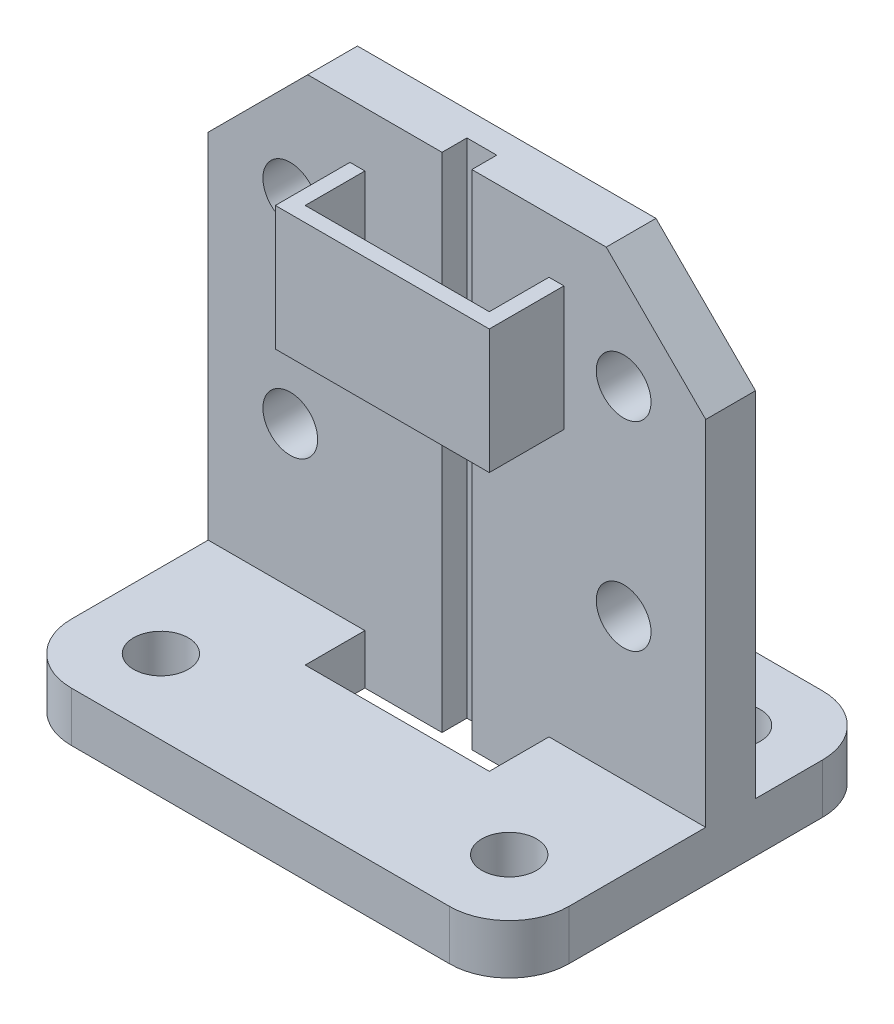
SolidWorks part; units mm, degrees
ref_plane "Front Plane" through (0, 0, 0) normal (0, 0, 1) x (1, 0, 0)
ref_plane "Top Plane" through (0, 0, 0) normal (0, 1, 0) x (1, 0, 0)
ref_plane "Right Plane" through (0, 0, 0) normal (1, 0, 0) x (0, 0, -1)
sketch "Sketch1" plane through (0, 0, 0) normal (0, 0, 1) x (1, 0, 0)
  line L1 (12.7, -10.795) -> (-12.7, -10.795)
  line L2 (12.7, -10.795) -> (12.7, 10.795)
  line L3 (12.7, 10.795) -> (-12.7, 10.795)
  line L4 (-12.7, -10.795) -> (-12.7, 10.795)
  line L5 (12.7, -10.795) -> (-12.7, 10.795) construction
  line L6 (12.7, 10.795) -> (-12.7, -10.795) construction
  line L7 (8.509, -5.08) -> (-8.509, -5.08) construction
  line L8 (8.509, -5.08) -> (8.509, 5.08) construction
  line L9 (8.509, 5.08) -> (-8.509, 5.08) construction
  line L10 (-8.509, -5.08) -> (-8.509, 5.08) construction
  line L11 (8.509, -5.08) -> (-8.509, 5.08) construction
  line L12 (8.509, 5.08) -> (-8.509, -5.08) construction
  circle A0 centre (-8.509, 5.08) radius 1.397
  circle A1 centre (8.509, 5.08) radius 1.397
  circle A2 centre (8.509, -5.08) radius 1.397
  circle A3 centre (-8.509, -5.08) radius 1.397
  point P0 (0, 0)
  point P6 (0, 0)
  dimension "D5" = 2.794
  dimension "D1" = 25.4
  dimension "D2" = 21.59
  dimension "D3" = 17.018
  dimension "D4" = 10.16
extrude "Boss-Extrude1" add sketch "Sketch1" along normal blind 2.54
sketch "Sketch2" plane through (0, 0, 2.54) normal (0, 0, 1) x (1, 0, 0)
  line L0 (12.7, 10.795) -> (-12.7, 10.795) construction
  line L1 (0.762, -10.795) -> (-0.762, -10.795)
  line L2 (0.762, -10.795) -> (0.762, 10.795)
  line L3 (0.762, 10.795) -> (-0.762, 10.795)
  line L4 (-0.762, -10.795) -> (-0.762, 10.795)
  line L5 (0.762, -10.795) -> (-0.762, 10.795) construction
  line L6 (0.762, 10.795) -> (-0.762, -10.795) construction
  point P0 (0, 0)
  dimension "D1" = 1.524
extrude "Cut-Extrude1" cut sketch "Sketch2" against normal blind 1.27
ref_plane "Plane1" through (0, -1.905, 0) normal (0, -1, 0) x (-1, 0, 0)
sketch "Sketch5" plane through (0, -1.905, 0) normal (0, -1, 0) x (-1, 0, 0)
  line L0 (-4.445, -2.54) -> (-4.445, -5.334)
  line L1 (-0.762, -2.54) -> (-12.7, -2.54) construction
  line L2 (-4.445, -5.334) -> (4.445, -5.334)
  line L3 (4.445, -5.334) -> (4.445, -2.54)
  line L4 (12.7, -2.54) -> (0.762, -2.54) construction
  line L5 (4.445, -2.54) -> (0.762, -2.54) construction
  line L9 (-0.762, -2.54) -> (-4.445, -2.54) construction
  line L10 (-4.445, -2.54) -> (-4.699, -2.54)
  line L11 (-4.699, -2.54) -> (-4.699, -5.588)
  line L12 (-4.699, -5.588) -> (4.699, -5.588)
  line L13 (4.699, -5.588) -> (4.699, -2.54)
  line L14 (4.699, -2.54) -> (4.445, -2.54)
  line L15 (0, 0) -> (0, -5.588) construction
  dimension "D1" = 8.89
  dimension "D2" = 2.794
  dimension "D3" = 0.254
  dimension "D4" = 0.254
sketch "Sketch7" plane through (0, -10.795, 0) normal (0, -1, 0) x (1, 0, 0)
  line L0 (-0.762, 2.54) -> (-12.7, 2.54)
  line L1 (-12.7, 2.54) -> (-12.7, 0)
  line L2 (-12.7, 0) -> (12.7, 0)
  line L3 (12.7, 0) -> (12.7, 2.54)
  line L4 (12.7, 2.54) -> (0.762, 2.54)
  line L5 (0.762, 2.54) -> (0.762, 1.27)
  line L6 (0.762, 1.27) -> (-0.762, 1.27)
  line L7 (-0.762, 1.27) -> (-0.762, 2.54)
extrude "Boss-Extrude3" add sketch "Sketch7" along normal blind 1.524
sketch "Sketch8" plane through (0, -12.319, 0) normal (0, -1, 0) x (1, 0, 0)
  line L0 (0, 3.048) -> (0, 0) construction
  line L1 (12.7, -6.477) -> (-12.7, -6.477)
  line L2 (12.7, -6.477) -> (12.7, 12.573)
  line L3 (12.7, 12.573) -> (-12.7, 12.573)
  line L4 (-12.7, -6.477) -> (-12.7, 12.573)
  line L5 (12.7, -6.477) -> (-12.7, 12.573) construction
  line L6 (12.7, 12.573) -> (-12.7, -6.477) construction
  line L8 (-12.7, 0) -> (12.7, 0) construction
  circle A0 centre (-8.89, 8.763) radius 1.397
  circle A1 centre (8.89, 8.763) radius 1.397
  circle A2 centre (-8.89, -2.667) radius 1.397
  circle A3 centre (8.89, -2.667) radius 1.397
  point P0 (0, 3.048)
  dimension "D3" = 2.794
  dimension "D1" = 25.4
  dimension "D2" = 19.05
  dimension "D4" = 3.81
  dimension "D5" = 3.81
  dimension "D6" = 3.81
  dimension "D7" = 3.81
  dimension "D8" = 3.048
extrude "Boss-Extrude4" add sketch "Sketch8" along normal blind 2.54
extrude "Cut-Extrude2" cut sketch "Sketch5" along normal blind 15.24
sketch "Sketch9" plane through (0, -12.319, 0) normal (0, 1, 0) x (1, 0, 0)
  line L0 (-0.762, -1.27) -> (0.762, -1.27)
  line L1 (0.762, -1.27) -> (0.762, -2.54)
  line L2 (0.762, -2.54) -> (4.445, -2.54)
  line L3 (4.445, -2.54) -> (4.445, -5.334)
  line L4 (4.445, -5.334) -> (-4.445, -5.334)
  line L5 (-4.445, -5.334) -> (-4.445, -2.54)
  line L6 (-4.445, -2.54) -> (-0.762, -2.54)
  line L7 (-0.762, -2.54) -> (-0.762, -1.27)
extrude "Cut-Extrude3" cut sketch "Sketch9" against normal blind 15.24
ref_plane "Plane2" through (0, 1.651, 0) normal (0, 1, 0) x (1, 0, 0)
sketch "Sketch11" plane through (0, 1.651, 0) normal (0, 1, 0) x (1, 0, 0)
  line L0 (-4.699, -2.54) -> (-5.461, -2.54)
  line L1 (-0.762, -2.54) -> (-12.7, -2.54) construction
  line L2 (-5.461, -2.54) -> (-5.461, -6.35)
  line L3 (-5.461, -6.35) -> (5.461, -6.35)
  line L4 (5.461, -6.35) -> (5.461, -2.54)
  line L6 (5.461, -2.54) -> (4.699, -2.54)
  line L7 (4.699, -2.54) -> (4.699, -5.588)
  line L8 (4.699, -5.588) -> (-4.699, -5.588)
  line L9 (-4.699, -5.588) -> (-4.699, -2.54)
  dimension "D1" = 0.762
  dimension "D2" = 0.762
extrude "Boss-Extrude5" add sketch "Sketch11" along normal blind 6.35
chamfer "Chamfer1" distance 5.08 angle 45 2 edges at (12.7, 10.795, 1.27) (-12.7, 10.795, 1.27)
fillet "Fillet1" radius 3.048 4 edges at (12.7, -13.589, -6.477) (-12.7, -13.589, -6.477) (-12.7, -13.589, 12.573) (12.7, -13.589, 12.573)
